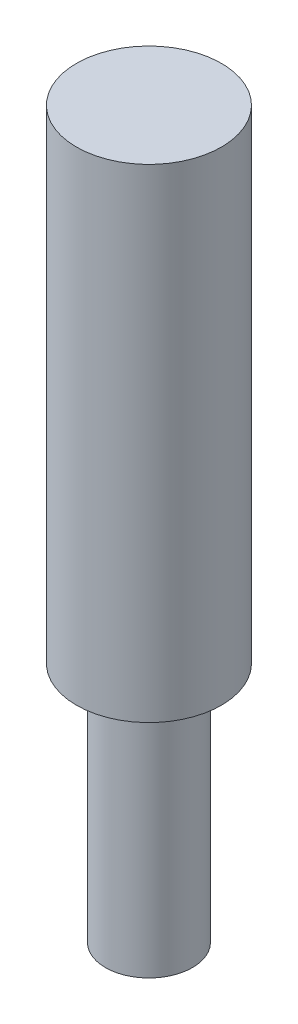
SolidWorks part; units mm, degrees
ref_plane "前视基准面" through (0, 0, 0) normal (0, 0, 1) x (1, 0, 0)
ref_plane "上视基准面" through (0, 0, 0) normal (0, 1, 0) x (1, 0, 0)
ref_plane "右视基准面" through (0, 0, 0) normal (1, 0, 0) x (0, 0, -1)
other "Configuration Table"
sketch "草图1" plane through (0, 0, 0) normal (0, 1, 0) x (1, 0, 0)
  circle A0 centre (0, 0) radius 0.9
  dimension "D1" = 1.8
extrude "凸台-拉伸1" add sketch "草图1" along normal blind 5
sketch "草图2" plane through (0, 5, 0) normal (0, 1, 0) x (1, 0, 0)
  circle A0 centre (0, 0) radius 1.5
  dimension "D1" = 3
extrude "凸台-拉伸2" add sketch "草图2" along normal blind 10
